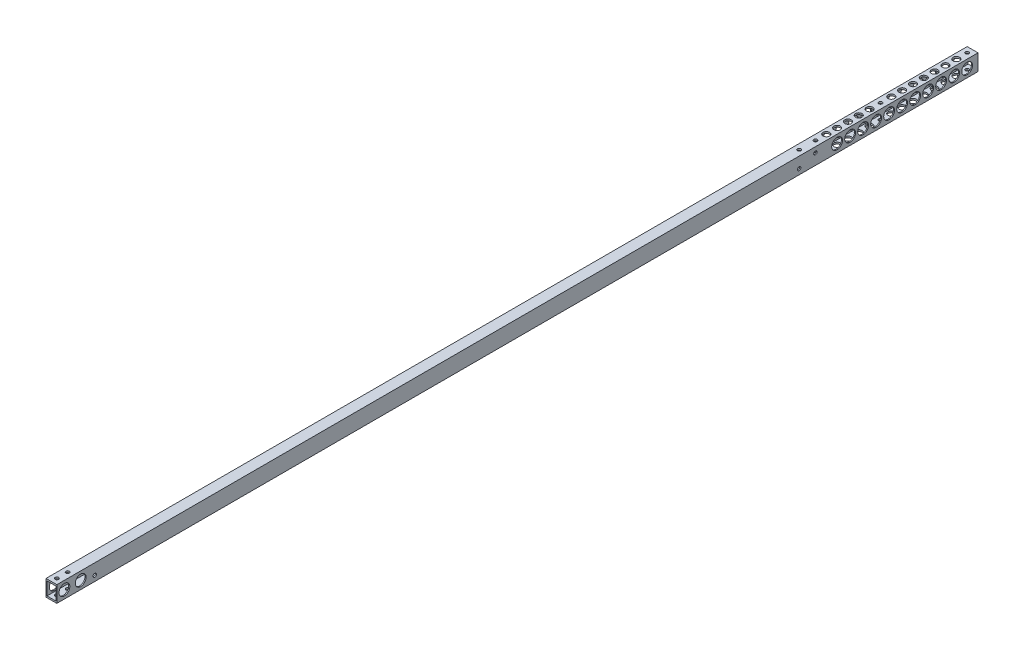
SolidWorks part; units mm, degrees
material "6061 合金"
ref_plane "正面" through (0, 0, 0) normal (0, 0, 1) x (1, 0, 0)
ref_plane "平面" through (0, 0, 0) normal (0, 1, 0) x (1, 0, 0)
ref_plane "右側面" through (0, 0, 0) normal (1, 0, 0) x (0, 0, -1)
sketch "ｽｹｯﾁ1" plane through (0, 0, 0) normal (0, 0, 1) x (1, 0, 0)
  line L5 (-5, -7.5) -> (5, -7.5)
  line L6 (-5, -7.5) -> (-5, 7.5)
  line L7 (-5, 7.5) -> (5, 7.5)
  line L8 (5, -7.5) -> (5, 7.5)
  line L9 (-5, -7.5) -> (5, 7.5) construction
  line L10 (-5, 7.5) -> (5, -7.5) construction
  line L11 (4, -6) -> (-4, -6)
  line L12 (4, -6) -> (4, 6)
  line L13 (4, 6) -> (-4, 6)
  line L14 (-4, -6) -> (-4, 6)
  line L15 (4, -6) -> (-4, 6) construction
  line L16 (4, 6) -> (-4, -6) construction
  point P0 (0, 0)
  point P7 (0, 0)
  dimension "D1" = 15
  dimension "D2" = 10
  dimension "D3" = 8
extrude "ﾎﾞｽ - 押し出し1" add sketch "ｽｹｯﾁ1" along normal blind 850
sketch "ｽｹｯﾁ2" plane through (-5, 0, 0) normal (-1, 0, 0) x (0, 0, 1)
  line L0 (0, 7.5) -> (0, -7.5) construction
  line L1 (850, -7.5) -> (0, -7.5) construction
  line L2 (850, 7.5) -> (850, -7.5) construction
  circle A0 centre (165, -2.5) radius 1.6
  circle A1 centre (815, -2.5) radius 1.6
  circle A2 centre (150, 2.5) radius 1.6
  dimension "D1" = 3.2
  dimension "D2" = 3.2
  dimension "D3" = 35
  dimension "D4" = 5
  dimension "D5" = 5
  dimension "D6" = 650
  dimension "D7" = 3.2
  dimension "D8" = 10
  dimension "D9" = 150
extrude "ｶｯﾄ - 押し出し1" cut sketch "ｽｹｯﾁ2" against normal through all
sketch "ｽｹｯﾁ3" plane through (5, 0, 0) normal (1, 0, 0) x (0, 0, -1)
  line L0 (-850, -7.5) -> (0, -7.5) construction
  line L1 (-850, -7.5) -> (-850, 7.5) construction
  circle A0 centre (-843, 0) radius 5
  dimension "D1" = 10
  dimension "D2" = 7.5
  dimension "D3" = 7
extrude "ｶｯﾄ - 押し出し2" cut sketch "ｽｹｯﾁ3" against normal through all
sketch "ｽｹｯﾁ4" plane through (0, 7.5, 0) normal (0, 1, 0) x (1, 0, 0)
  line L0 (5, -850) -> (-5, -850) construction
  line L1 (5, -850) -> (5, 0) construction
  circle A0 centre (0, -845) radius 1.6
  circle A1 centre (0, -835) radius 1.6
  dimension "D1" = 3.2
  dimension "D2" = 5
  dimension "D3" = 5
  dimension "D4" = 3.2
  dimension "D5" = 10
  dimension "D6" = 5
extrude "ｶｯﾄ - 押し出し3" cut sketch "ｽｹｯﾁ4" against normal through all
sketch "ｽｹｯﾁ7" plane through (0, -7.5, 0) normal (0, -1, 0) x (-1, 0, 0)
  line L0 (5, 0) -> (-5, 0) construction
  line L1 (5, -850) -> (5, 0) construction
  circle A0 centre (0, -5) radius 1.6
  circle A1 centre (0, -85) radius 1.6
  circle A2 centre (0, -145) radius 1.6
  dimension "D1" = 3.2
  dimension "D2" = 3.2
  dimension "D3" = 3.2
  dimension "D4" = 5
  dimension "D6" = 60
  dimension "D7" = 5
  dimension "D9" = 5
  dimension "D5" = 80
  dimension "D8" = 5
extrude "ｶｯﾄ - 押し出し6" cut sketch "ｽｹｯﾁ7" against normal through all
sketch "ｽｹｯﾁ8" plane through (5, 0, 0) normal (1, 0, 0) x (0, 0, -1)
  line L0 (0, -7.5) -> (0, 7.5) construction
  line L1 (-850, -7.5) -> (0, -7.5) construction
  circle A0 centre (-10, 0) radius 5
  dimension "D1" = 10
  dimension "D2" = 10
  dimension "D3" = 7.5
extrude "ｶｯﾄ - 押し出し7" cut sketch "ｽｹｯﾁ8" against normal through all
pattern_linear "直線ﾊﾟﾀｰﾝ1" count 11 spacing 12 along (0, 0, 1) of "ｶｯﾄ - 押し出し7"
sketch "ｽｹｯﾁ9" plane through (0, 7.5, 0) normal (0, 1, 0) x (1, 0, 0)
  line L0 (-5, -850) -> (-5, 0) construction
  circle A0 centre (0, -160) radius 1.6
  circle A1 centre (0, -145) radius 1.6 construction
  dimension "D1" = 5
  dimension "D2" = 3.2
  dimension "D3" = 15
extrude "ｶｯﾄ - 押し出し8" cut sketch "ｽｹｯﾁ9" against normal through all
pattern_linear "直線ﾊﾟﾀｰﾝ2" count 2 spacing 15 along (0, 0, -1) of "ｶｯﾄ - 押し出し2"
sketch "ｽｹｯﾁ10" plane through (0, -7.5, 0) normal (0, -1, 0) x (-1, 0, 0)
  line L0 (5, -850) -> (5, 0) construction
  line L1 (5, 0) -> (-5, 0) construction
  circle A0 centre (0, -15) radius 3
  dimension "D1" = 6
  dimension "D2" = 5
  dimension "D3" = 15
extrude "ｶｯﾄ - 押し出し9" cut sketch "ｽｹｯﾁ10" against normal through all
pattern_linear "直線ﾊﾟﾀｰﾝ3" count 7 spacing 10 along (0, 0, 1) of "ｶｯﾄ - 押し出し9"
sketch "ｽｹｯﾁ11" plane through (0, 7.5, 0) normal (0, 1, 0) x (1, 0, 0)
  line L0 (5, -850) -> (5, 0) construction
  circle A0 centre (0, -95) radius 3
  circle A1 centre (0, -85) radius 1.6 construction
  dimension "D1" = 6
  dimension "D2" = 5
  dimension "D3" = 10
extrude "ｶｯﾄ - 押し出し10" cut sketch "ｽｹｯﾁ11" against normal through all
pattern_linear "直線ﾊﾟﾀｰﾝ4" count 5 spacing 10 along (0, 0, 1) of "ｶｯﾄ - 押し出し10"
